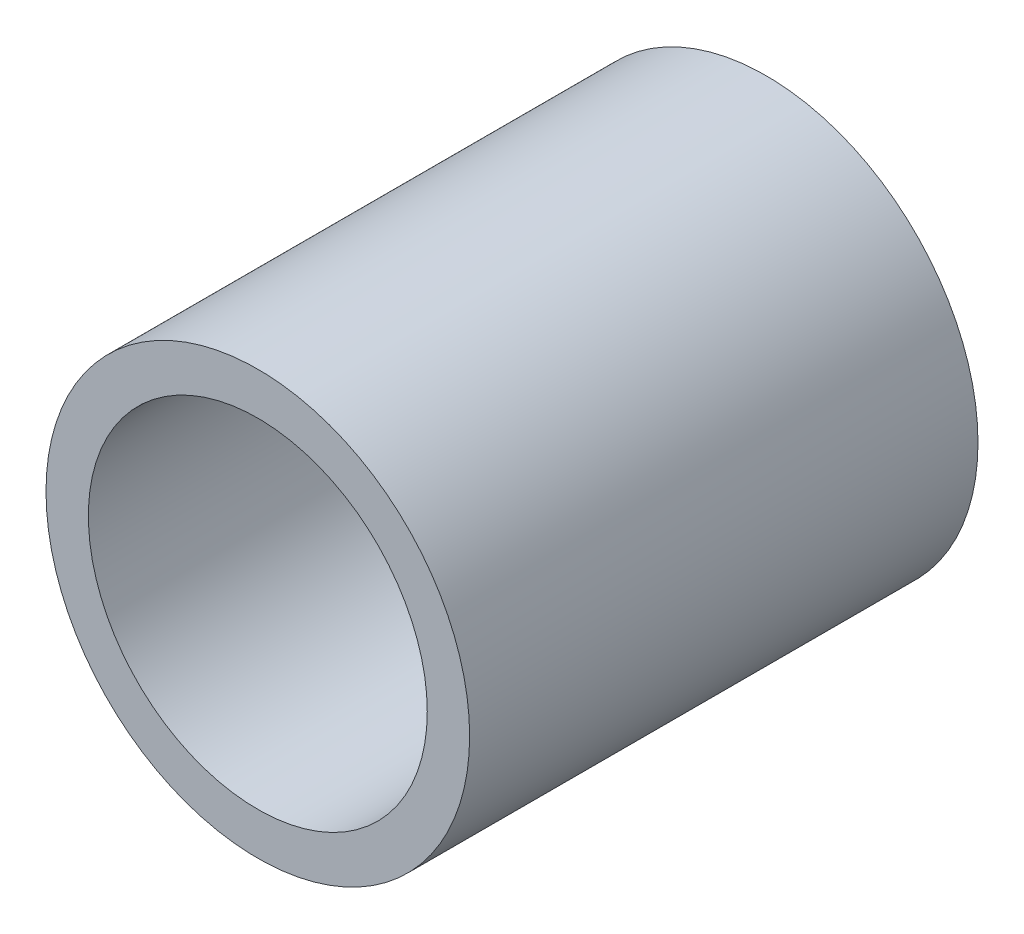
SolidWorks part; units mm, degrees
material "Bronce al estaño"
ref_plane "Alzado" through (0, 0, 0) normal (0, 0, 1) x (1, 0, 0)
ref_plane "Planta" through (0, 0, 0) normal (0, 1, 0) x (1, 0, 0)
ref_plane "Vista lateral" through (0, 0, 0) normal (1, 0, 0) x (0, 0, -1)
sketch "Croquis1" plane through (0, 0, 0) normal (1, 0, 0) x (0, 0, -1)
  line L0 (0, 0) -> (68.0147, 0) construction
  line L1 (0, 0) -> (0, 7.9375)
  line L2 (0, 7.9375) -> (19.05, 7.9375)
  line L3 (19.05, 7.9375) -> (19.05, 0)
  line L4 (19.05, 0) -> (0, 0)
  dimension "D1" = 19.05
  dimension "D2" = 15.875
revolve "Revolución1" add sketch "Croquis1" angle 360 about L0
sketch "Croquis2" plane through (0, 0, 0) normal (0, 0, 1) x (1, 0, 0)
  circle A0 centre (0, 0) radius 6.35
  dimension "D1" = 12.7
extrude "Cortar-Extruir2" cut sketch "Croquis2" against normal up to next
